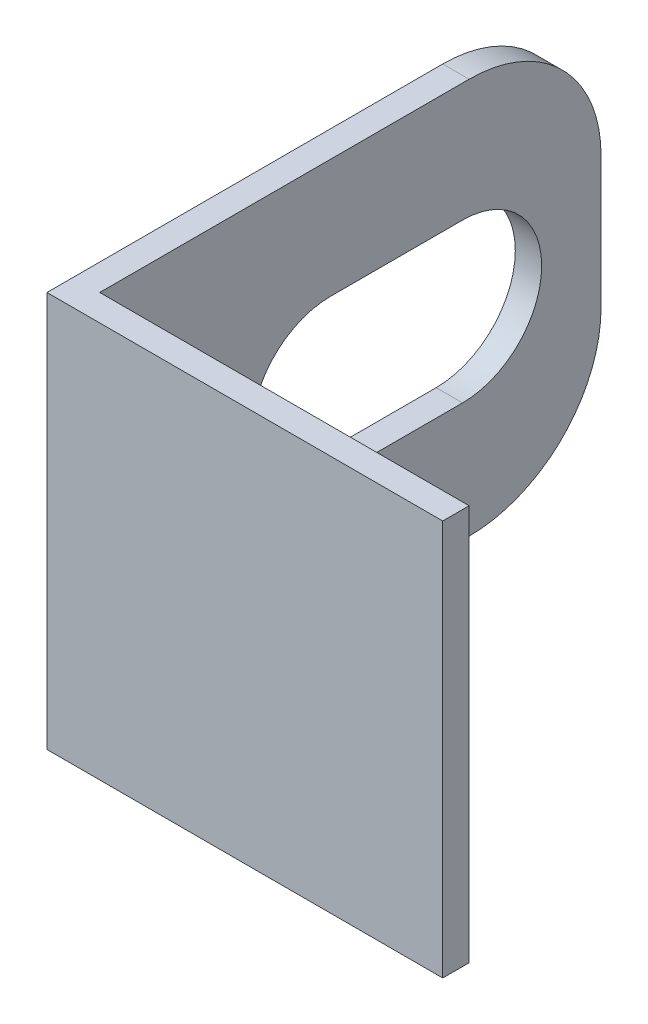
SolidWorks part; units mm, degrees
ref_plane "前视基准面" through (0, 0, 0) normal (0, 0, 1) x (1, 0, 0)
ref_plane "上视基准面" through (0, 0, 0) normal (0, 1, 0) x (1, 0, 0)
ref_plane "右视基准面" through (0, 0, 0) normal (1, 0, 0) x (0, 0, -1)
sketch "草图1" plane through (0, 0, 0) normal (0, 1, 0) x (1, 0, 0)
  line L1 (-1, -20) -> (1, -20)
  line L2 (-1, -20) -> (-1, 20)
  line L3 (-1, 20) -> (1, 20)
  line L4 (1, -20) -> (1, 20)
  line L5 (-1, -20) -> (1, 20) construction
  line L6 (-1, 20) -> (1, -20) construction
  line L7 (1, -20) -> (29, -20)
  line L8 (1, -20) -> (1, -18)
  line L9 (1, -18) -> (29, -18)
  line L10 (29, -20) -> (29, -18)
  point P0 (0, 0)
  dimension "D1" = 40
  dimension "D2" = 2
  dimension "D3" = 30
extrude "凸台-拉伸1" add sketch "草图1" along normal mid plane 30 contours L1 L4 L3 L2 | L7 L10 L9 L4
fillet "圆角1" radius 10 2 edges at (0, -15, -20) (0, 15, -20)
sketch "草图2" plane through (1, 0, 0) normal (1, 0, 0) x (0, 0, -1)
  line L1 (-0.5, 0) -> (9.5, 0) construction
  line L2 (-0.5, 6) -> (9.5, 6)
  line L3 (-0.5, -6) -> (9.5, -6)
  line L4 (-20, 15) -> (-20, -15) construction
  arc A0 (-0.5, 6) -> (-0.5, -6) centre (-0.5, 0) ccw
  arc A1 (9.5, -6) -> (9.5, 6) centre (9.5, 0) ccw
  point P2 (4.5, 0)
  dimension "D1" = 6
  dimension "D2" = 19.5
  dimension "D3" = 10
extrude "切除-拉伸1" cut sketch "草图2" against normal through all both and the other way through all
